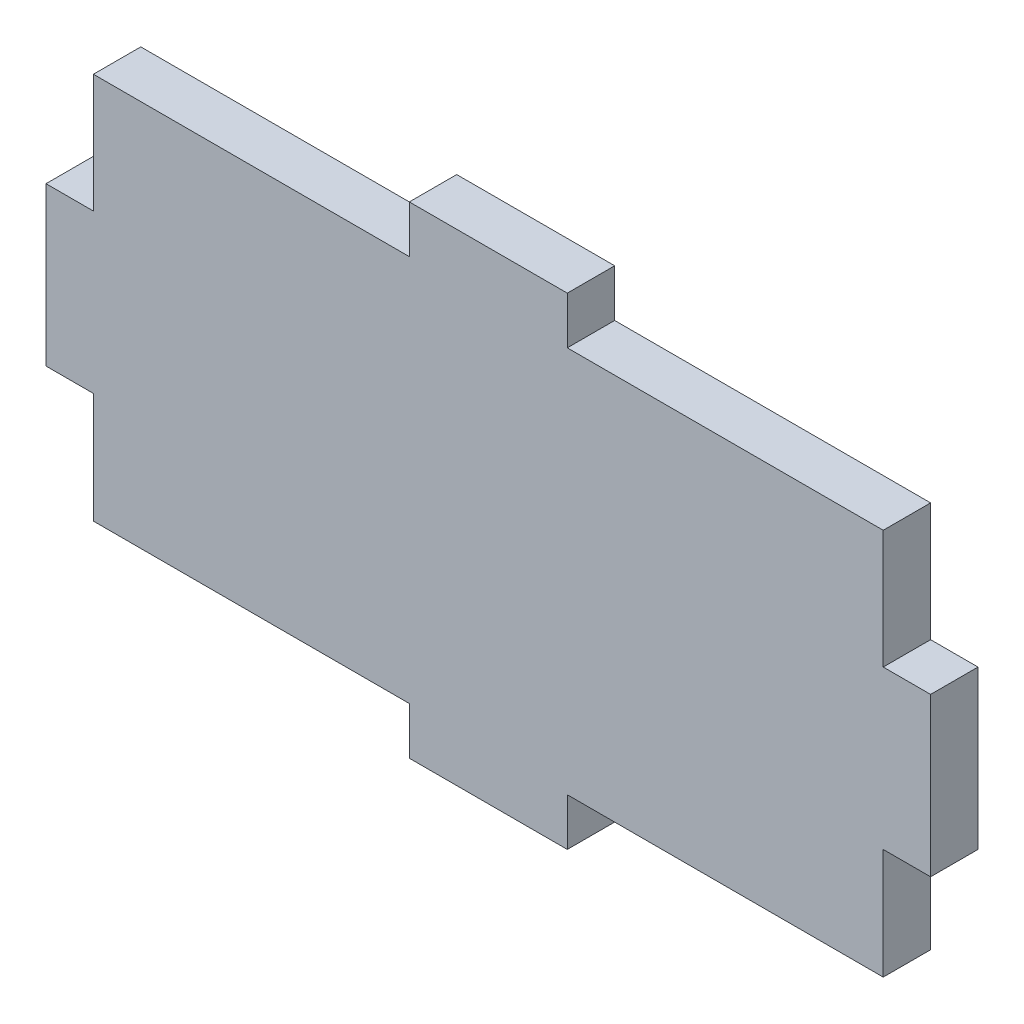
SolidWorks part; units mm, degrees
ref_plane "Front Plane" through (0, 0, 0) normal (0, 0, 1) x (1, 0, 0)
ref_plane "Top Plane" through (0, 0, 0) normal (0, 1, 0) x (1, 0, 0)
ref_plane "Right Plane" through (0, 0, 0) normal (1, 0, 0) x (0, 0, -1)
sketch "Sketch1" plane through (0, 0, 0) normal (0, 0, 1) x (-1, 0, 0)
  line L0 (-3.4763, -8.3376) -> (-3.4763, -5.3376)
  line L1 (-3.4763, -5.3376) -> (6.5237, -5.3376)
  line L2 (6.5237, -8.3376) -> (26.5237, -8.3376)
  line L3 (26.5237, -8.3376) -> (26.5237, -15.3376)
  line L4 (26.5237, -15.3376) -> (29.5237, -15.3376)
  line L5 (29.5237, -15.3376) -> (29.5237, -25.3376)
  line L6 (29.5237, -25.3376) -> (26.5237, -25.3376)
  line L7 (26.5237, -25.3376) -> (26.5237, -32.8376)
  line L8 (29.0237, -2.8376) -> (46.0636, -20.3376) construction
  line L9 (6.5237, -5.3376) -> (6.5237, -8.3376)
  line L10 (-3.4763, -8.3376) -> (-23.4763, -8.3376)
  line L11 (46.0636, -20.3376) -> (29.0237, -37.8376) construction
  line L12 (1.5237, -5.3376) -> (1.5237, -64.0619) construction
  line L13 (-23.4763, -25.3376) -> (-23.4763, -32.8376)
  line L14 (-26.4763, -25.3376) -> (-23.4763, -25.3376)
  line L15 (-26.4763, -15.3376) -> (-26.4763, -25.3376)
  line L16 (-23.4763, -15.3376) -> (-26.4763, -15.3376)
  line L17 (-23.4763, -8.3376) -> (-23.4763, -15.3376)
  line L18 (-26.4763, -20.3376) -> (-16.6963, -20.3376) construction
  line L19 (26.5237, -32.8376) -> (26.5237, -39.8376) construction
  line L20 (12.5029, -8.3376) -> (12.5029, -32.8376) construction
  line L21 (12.5029, -20.5876) -> (75.1393, -20.5876) construction
  line L22 (-3.4763, -32.8376) -> (-23.4763, -32.8376)
  line L23 (6.5237, -35.8376) -> (6.5237, -32.8376)
  line L24 (6.5237, -32.8376) -> (26.5237, -32.8376)
  line L25 (-3.4763, -35.8376) -> (6.5237, -35.8376)
  line L26 (-3.4763, -32.8376) -> (-3.4763, -35.8376)
  dimension "D1" = 20
  dimension "D2" = 3
  dimension "D3" = 10
  dimension "D4" = 10
  dimension "D5" = 3
  dimension "D6" = 50
  dimension "D7" = 7
  dimension "D8" = 7.5
extrude "Boss-Extrude1" add sketch "Sketch1" along normal blind 3
